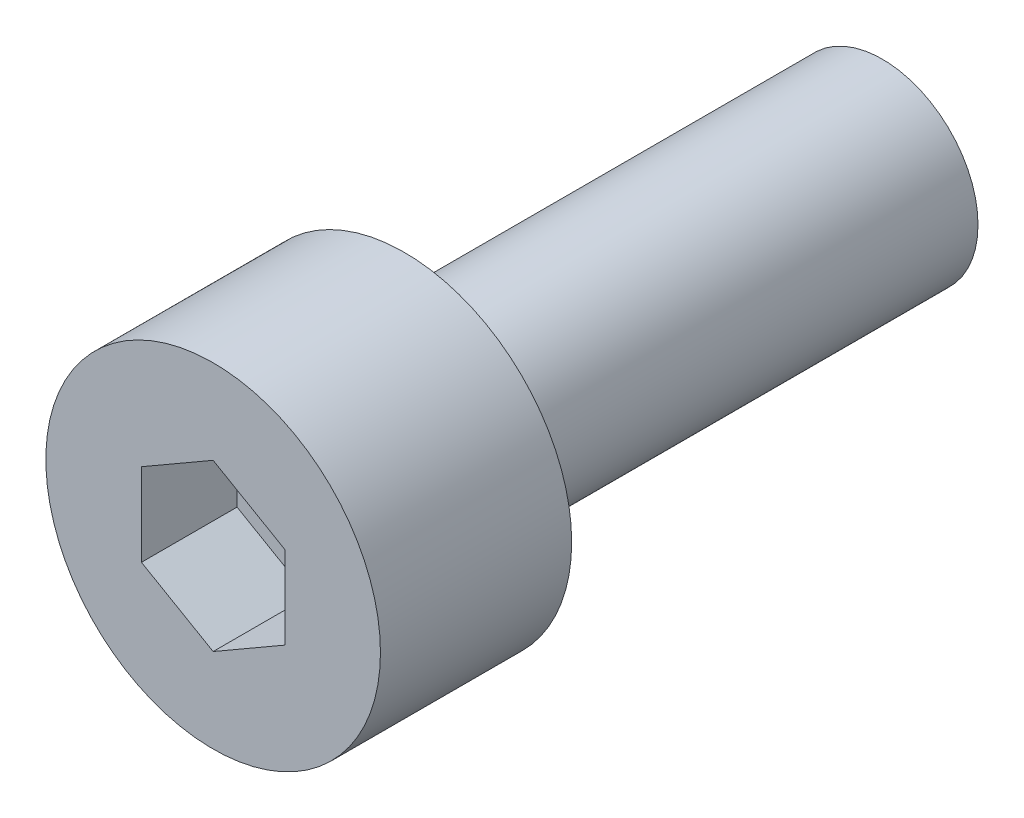
SolidWorks part; units mm, degrees
ref_plane "Alzado" through (0, 0, 0) normal (0, 0, 1) x (1, 0, 0)
ref_plane "Planta" through (0, 0, 0) normal (0, 1, 0) x (1, 0, 0)
ref_plane "Vista lateral" through (0, 0, 0) normal (1, 0, 0) x (0, 0, -1)
sketch "Croquis1" plane through (0, 0, 0) normal (0, 0, 1) x (1, 0, 0)
  circle A0 centre (0, 0) radius 3.5
  dimension "D1" = 7
extrude "Saliente-Extruir1" add sketch "Croquis1" along normal blind 4
sketch "Croquis2" plane through (0, 0, 4) normal (0, 0, 1) x (1, 0, 0)
  line L1 (1.5, 0.866) -> (0, 1.7321)
  line L2 (0, 1.7321) -> (-1.5, 0.866)
  line L3 (-1.5, 0.866) -> (-1.5, -0.866)
  line L4 (-1.5, -0.866) -> (0, -1.7321)
  line L5 (0, -1.7321) -> (1.5, -0.866)
  line L6 (1.5, -0.866) -> (1.5, 0.866)
  circle A0 centre (0, 0) radius 1.5 construction
  dimension "D1" = 3
extrude "Cortar-Extruir1" cut sketch "Croquis2" against normal blind 2
sketch "Croquis3" plane through (0, 0, 0) normal (0, 0, -1) x (-1, 0, 0)
  circle A0 centre (0, 0) radius 2
  dimension "D1" = 4
extrude "Saliente-Extruir2" add sketch "Croquis3" along normal blind 10
